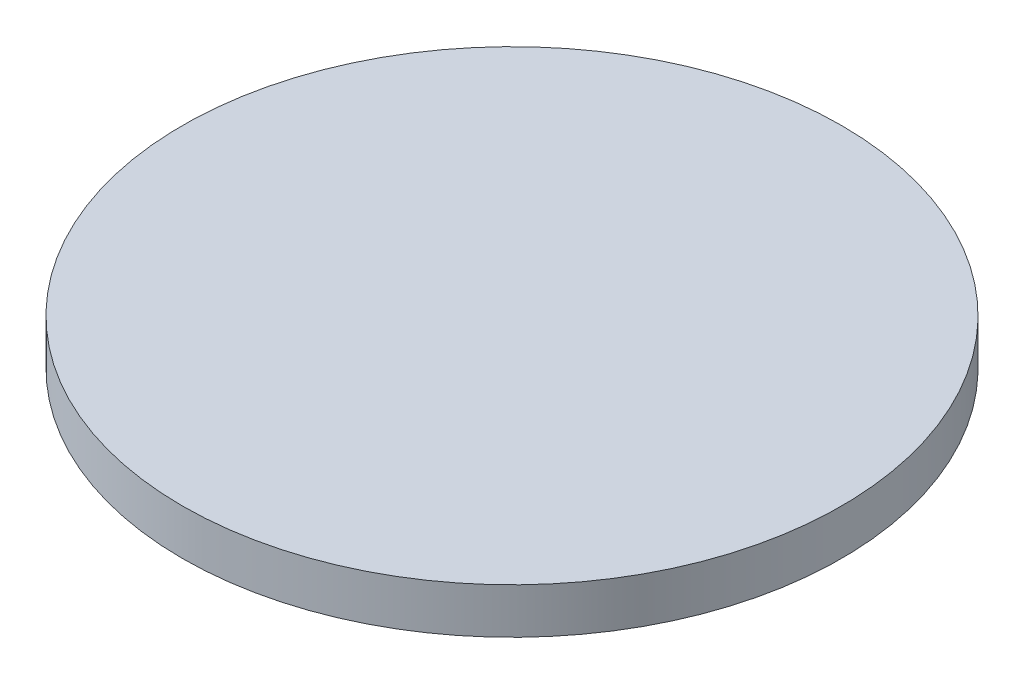
SolidWorks part; units mm, degrees
ref_plane "Front Plane" through (0, 0, 0) normal (0, 0, 1) x (1, 0, 0)
ref_plane "Top Plane" through (0, 0, 0) normal (0, 1, 0) x (1, 0, 0)
ref_plane "Right Plane" through (0, 0, 0) normal (1, 0, 0) x (0, 0, -1)
sketch "Sketch1" plane through (0, 0, 0) normal (0, 1, 0) x (1, 0, 0)
  circle A0 centre (0, 0) radius 11.5
  dimension "D1" = 23
extrude "Boss-Extrude1" add sketch "Sketch1" along normal blind 1.5875
